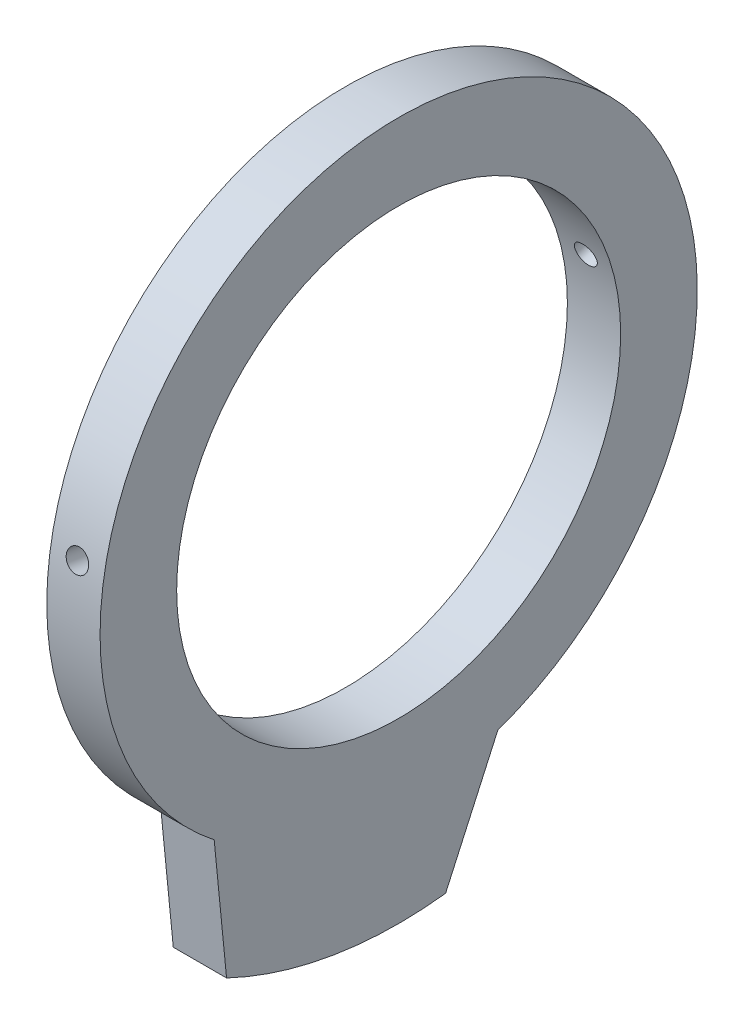
SolidWorks part; units mm, degrees
ref_plane "正面" through (0, 0, 0) normal (0, 0, 1) x (1, 0, 0)
ref_plane "平面" through (0, 0, 0) normal (0, 1, 0) x (1, 0, 0)
ref_plane "右側面" through (0, 0, 0) normal (1, 0, 0) x (0, 0, -1)
sketch "ｽｹｯﾁ1" plane through (0, 0, 0) normal (1, 0, 0) x (0, 0, -1)
  circle A0 centre (0, 0) radius 67.25
extrude "ﾎﾞｽ - 押し出し1" add sketch "ｽｹｯﾁ1" along normal blind 12
sketch "ｽｹｯﾁ2" plane through (0, 0, 0) normal (1, 0, 0) x (0, 0, -1)
  line L0 (-41.5494, -52.8792) -> (-38.7584, -81.2267)
  line L1 (10.5697, -89.3772) -> (22.3283, -63.4351)
  line L2 (22.3283, -63.4351) -> (-41.5494, -52.8792)
  arc A0 (-38.7584, -81.2267) -> (10.5697, -89.3772) centre (0, 0) ccw
extrude "ﾎﾞｽ - 押し出し2" add sketch "ｽｹｯﾁ2" along normal blind 12
sketch "ｽｹｯﾁ3" plane through (0, 0, 0) normal (1, 0, 0) x (0, 0, -1)
  circle A0 centre (0, 0) radius 50
extrude "ｶｯﾄ - 押し出し1" cut sketch "ｽｹｯﾁ3" against normal through all and the other way through all
ref_plane "平面1" through (6, 0, 0) normal (1, 0, 0) x (0, 0, -1)
sketch "ｽｹｯﾁ4" plane through (6, 0, 0) normal (1, 0, 0) x (0, 0, -1)
  line L0 (-44.3993, 7.328) -> (-73.9989, 12.2133)
  line L1 (-73.9989, 12.2133) -> (-74.406, 9.7467)
  line L2 (-74.406, 9.7467) -> (-44.8064, 4.8614)
  line L3 (-44.8064, 4.8614) -> (-44.3993, 7.328)
  line L4 (0, 0) -> (-83.8654, 13.8418) construction
revolve "ｶｯﾄ - 回転1" cut sketch "ｽｹｯﾁ4" angle 360 about L4
sketch "ｽｹｯﾁ5" plane through (6, 0, 0) normal (1, 0, 0) x (0, 0, -1)
  line L0 (43.3389, 12.1136) -> (72.2315, 20.1894)
  line L1 (72.2315, 20.1894) -> (71.5585, 22.5971)
  line L2 (71.5585, 22.5971) -> (42.6659, 14.5214)
  line L3 (42.6659, 14.5214) -> (43.3389, 12.1136)
  line L4 (0, 0) -> (81.8624, 22.8813) construction
revolve "ｶｯﾄ - 回転2" cut sketch "ｽｹｯﾁ5" angle 360 about L4
